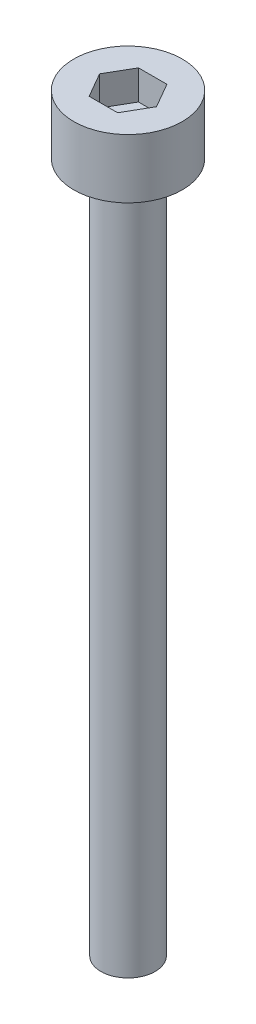
SolidWorks part; units mm, degrees
material "AISI 316 Stainless Steel Sheet (SS)"
ref_plane "Front Plane" through (0, 0, 0) normal (0, 0, 1) x (1, 0, 0)
ref_plane "Top Plane" through (0, 0, 0) normal (0, 1, 0) x (1, 0, 0)
ref_plane "Right Plane" through (0, 0, 0) normal (1, 0, 0) x (0, 0, -1)
sketch "Sketch1" plane through (0, 0, 0) normal (0, 0, 1) x (1, 0, 0)
  line L0 (0, 3) -> (-2.75, 3)
  line L1 (-2.75, 3) -> (-2.75, 0)
  line L2 (-2.75, 0) -> (-1.375, 0)
  line L3 (-1.375, 0) -> (-1.375, -35)
  line L4 (-1.375, -35) -> (0, -35)
  line L5 (0, -35) -> (0, 3)
  line L6 (0, -35) -> (0, -19.4894) construction
  dimension "D1" = 2.75
  dimension "D2" = 3
  dimension "D3" = 5.5
  dimension "D4" = 35
revolve "Revolve1" add sketch "Sketch1" angle 360 about L6
sketch "Sketch2" plane through (0, 3, 0) normal (0, 1, 0) x (1, 0, 0)
  line L1 (0.7217, -1.25) -> (1.4434, 0)
  line L2 (1.4434, 0) -> (0.7217, 1.25)
  line L3 (0.7217, 1.25) -> (-0.7217, 1.25)
  line L4 (-0.7217, 1.25) -> (-1.4434, 0)
  line L5 (-1.4434, 0) -> (-0.7217, -1.25)
  line L6 (-0.7217, -1.25) -> (0.7217, -1.25)
  circle A0 centre (0, 0) radius 1.25 construction
  dimension "D1" = 2.5
extrude "Cut-Extrude1" cut sketch "Sketch2" against normal blind 1.5
